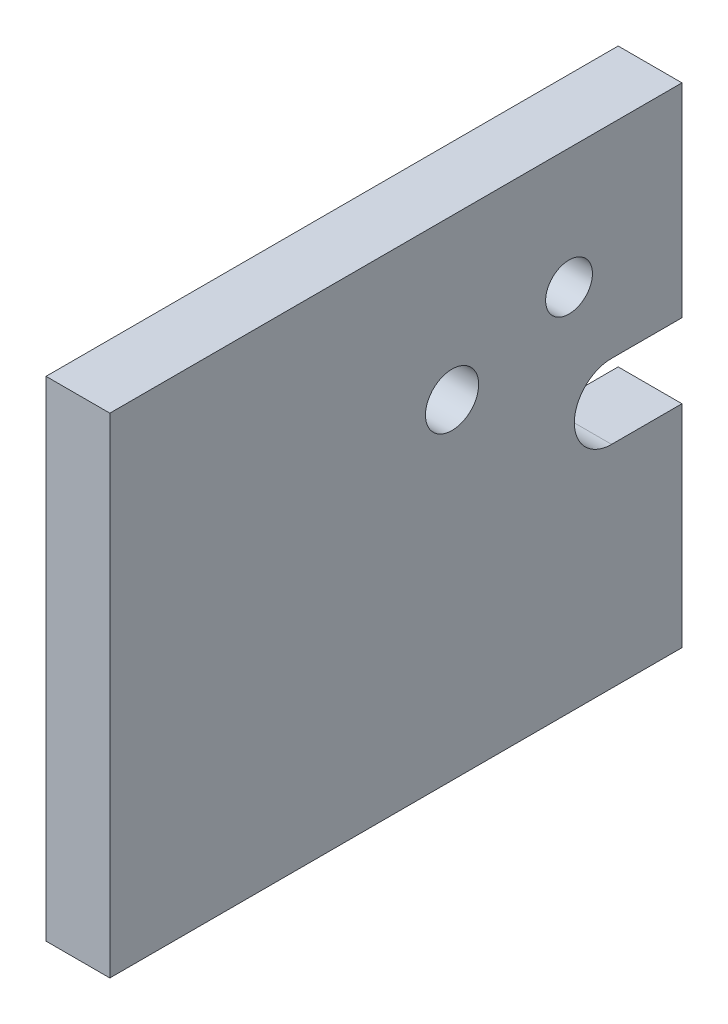
SolidWorks part; units mm, degrees
ref_plane "前视基准面" through (0, 0, 0) normal (0, 0, 1) x (1, 0, 0)
ref_plane "上视基准面" through (0, 0, 0) normal (0, 1, 0) x (1, 0, 0)
ref_plane "右视基准面" through (0, 0, 0) normal (1, 0, 0) x (0, 0, -1)
other "Configuration Table"
sketch "草图1" plane through (0, 0, 0) normal (1, 0, 0) x (0, 0, -1)
  line L1 (0, 0) -> (5, 0)
  line L2 (0, 0) -> (0, -5)
  line L3 (0, -5) -> (5, -5)
  line L4 (5, 0) -> (5, -5)
  line L5 (0, 0) -> (5, -5) construction
  circle A0 centre (2.5, -2.5) radius 1.1
  dimension "D1" = 5
  dimension "D3" = 2.2
  dimension "D2" = 5
extrude "凸台-拉伸1" add sketch "草图1" along normal blind 3 contours L1 L5 A0 L4 | L5 L2 L3 A0
sketch "草图2" plane through (0, 0, 0) normal (-1, 0, 0) x (0, 0, 1)
  line L0 (-5, 0) -> (-5, -5) construction
  line L1 (-5, 0) -> (-7.8098, 0)
  line L2 (-5, 0) -> (-5, 3.1588)
  line L3 (-5, 3.1588) -> (-7.8098, 3.1588)
  line L4 (-7.8098, 0) -> (-7.8098, 3.1588)
  line L5 (0, -5) -> (-5, -5) construction
  line L6 (-5, 3.1588) -> (19.0902, 3.1588)
  line L7 (-5, 3.1588) -> (-5, 0)
  line L8 (-5, 0) -> (19.0902, 0)
  line L9 (19.0902, 3.1588) -> (19.0902, 0)
  line L10 (-5, 0) -> (-7.8098, 0)
  line L11 (-5, 0) -> (-5, -19.8412)
  line L12 (-5, -19.8412) -> (-7.8098, -19.8412)
  line L13 (-7.8098, 0) -> (-7.8098, -19.8412)
  line L14 (-5, -19.8412) -> (19.0902, -19.8412)
  line L15 (-5, -19.8412) -> (-5, -5)
  line L16 (-5, -5) -> (19.0902, -5)
  line L17 (19.0902, -19.8412) -> (19.0902, -5)
  line L19 (0, -5) -> (19.0902, -5)
  line L20 (0, -5) -> (0, 0)
  line L21 (0, 0) -> (19.0902, 0)
  line L22 (19.0902, -5) -> (19.0902, 0)
  line L24 (-4.5, -6.4069) -> (-7.8098, -6.4069)
  line L25 (-7.8098, -6.4069) -> (-7.8098, -9.9069)
  line L26 (-7.8098, -9.9069) -> (-4.5, -9.9069)
  circle A0 centre (3, -4.3412) radius 1.25
  circle A1 centre (-4.5, -8.1569) radius 1.75
  line M7 (0, 0) -> (-5, 0)
  line M8 (-5, 0) -> (-5, -5)
  line M9 (-5, -5) -> (0, -5)
  line M10 (0, -5) -> (0, 0)
  dimension "D6" = 2.5
  dimension "D7" = 3.5
  dimension "D1" = 3.1588
  dimension "D2" = 2.8098
  dimension "D3" = 24.0902
  dimension "D4" = 19.8412
  dimension "D5" = 24.0902
extrude "凸台-拉伸2" add sketch "草图2" against normal up to surface (3 mm away) contours L4 L1 L2 L3 | L9 L6 L2 L8 M7 | L24 L11 L1 L13 M8 | A1 L26 L11 L14 L17 L16 A0 L24 M9 | A0 L16 L22 L8 M10 | L26 L13 L12 L11 up to face at (3, -2.5, -3.6)
